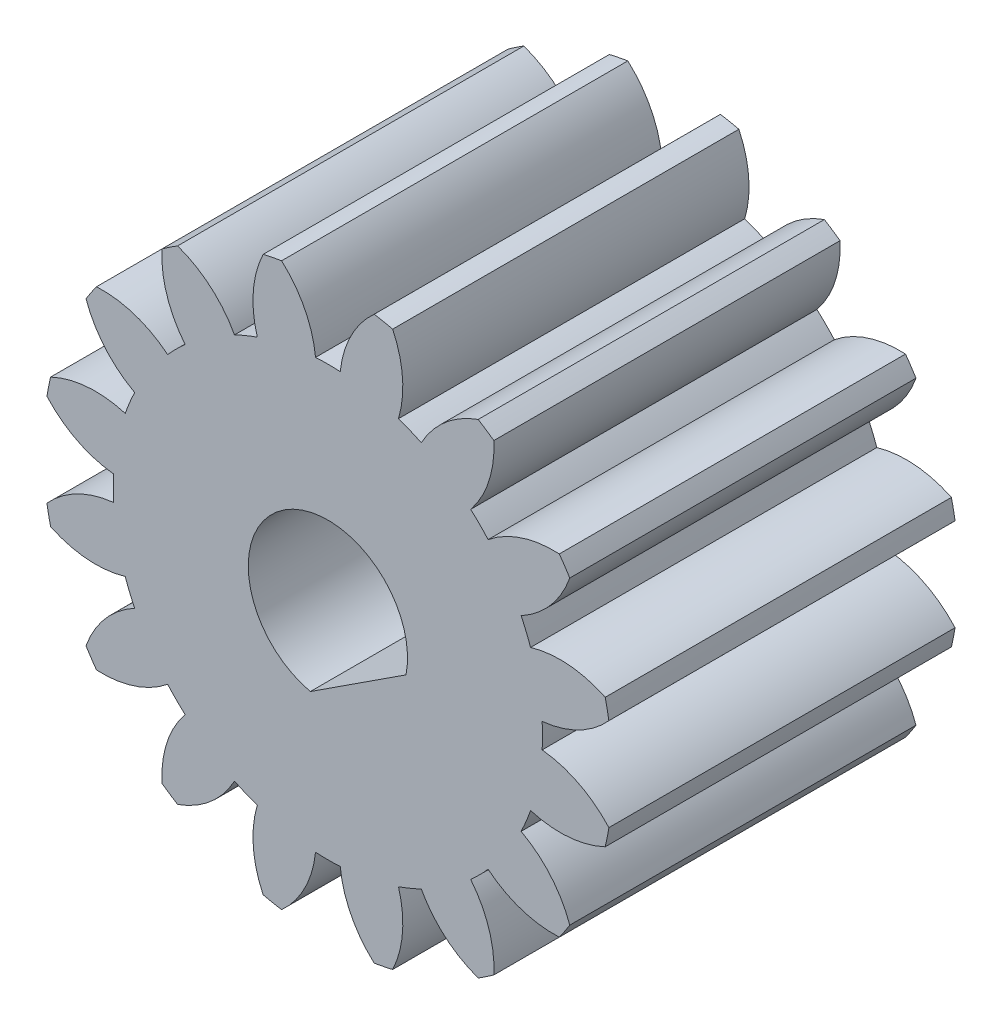
SolidWorks part; units mm, degrees
ref_plane "Front Plane" through (0, 0, 0) normal (0, 0, 1) x (1, 0, 0)
ref_plane "Top Plane" through (0, 0, 0) normal (0, 1, 0) x (1, 0, 0)
ref_plane "Right Plane" through (0, 0, 0) normal (1, 0, 0) x (0, 0, -1)
sketch "Model" plane through (0, 0, 0) normal (0, 0, 1) x (1, 0, 0)
  line L1 (-0.5062, -2.2436) -> (2.2564, -0.4458)
  arc A64 (-8.1156, 1.3371) -> (-6.1887, 0.3566) centre (-5.8806, 3.3458) ccw
  arc A65 (2.2564, -0.4458) -> (-0.5062, -2.2436) centre (0, 0) ccw
  arc A66 (-6.1887, 0.3566) -> (-6.1887, -0.3566) centre (0, 0) ccw
  arc A67 (-6.1887, -0.3566) -> (-8.1156, -1.3371) centre (-5.8806, -3.3458) ccw
  arc A68 (-8.1156, -1.3371) -> (-8.0095, -1.8704) centre (0, 0) ccw
  arc A69 (-8.0095, -1.8704) -> (-5.8541, -2.0388) centre (-6.7134, 0.8407) ccw
  arc A70 (-5.8541, -2.0388) -> (-5.5812, -2.6978) centre (0, 0) ccw
  arc A71 (-5.5812, -2.6978) -> (-6.9862, -4.341) centre (-4.1526, -5.3415) ccw
  arc A72 (-6.9862, -4.341) -> (-6.684, -4.7931) centre (0, 0) ccw
  arc A73 (-6.684, -4.7931) -> (-4.6283, -4.1239) centre (-6.524, -1.7924) ccw
  arc A74 (-4.6283, -4.1239) -> (-4.1239, -4.6283) centre (0, 0) ccw
  arc A75 (-4.1239, -4.6283) -> (-4.7931, -6.684) centre (-1.7924, -6.524) ccw
  arc A76 (-4.7931, -6.684) -> (-4.341, -6.9862) centre (0, 0) ccw
  arc A77 (-4.341, -6.9862) -> (-2.6978, -5.5812) centre (-5.3415, -4.1526) ccw
  arc A78 (-2.6978, -5.5812) -> (-2.0388, -5.8541) centre (0, 0) ccw
  arc A79 (-2.0388, -5.8541) -> (-1.8704, -8.0095) centre (0.8407, -6.7134) ccw
  arc A80 (-1.8704, -8.0095) -> (-1.3371, -8.1156) centre (0, 0) ccw
  arc A81 (-1.3371, -8.1156) -> (-0.3566, -6.1887) centre (-3.3458, -5.8806) ccw
  arc A82 (-0.3566, -6.1887) -> (0.3566, -6.1887) centre (0, 0) ccw
  arc A83 (0.3566, -6.1887) -> (1.3371, -8.1156) centre (3.3458, -5.8806) ccw
  arc A84 (1.3371, -8.1156) -> (1.8704, -8.0095) centre (0, 0) ccw
  arc A85 (1.8704, -8.0095) -> (2.0388, -5.8541) centre (-0.8407, -6.7134) ccw
  arc A86 (2.0388, -5.8541) -> (2.6978, -5.5812) centre (0, 0) ccw
  arc A87 (2.6978, -5.5812) -> (4.341, -6.9862) centre (5.3415, -4.1526) ccw
  arc A88 (4.341, -6.9862) -> (4.7931, -6.684) centre (0, 0) ccw
  arc A89 (4.7931, -6.684) -> (4.1239, -4.6283) centre (1.7924, -6.524) ccw
  arc A90 (4.1239, -4.6283) -> (4.6283, -4.1239) centre (0, 0) ccw
  arc A91 (4.6283, -4.1239) -> (6.684, -4.7931) centre (6.524, -1.7924) ccw
  arc A92 (6.684, -4.7931) -> (6.9862, -4.341) centre (0, 0) ccw
  arc A93 (6.9862, -4.341) -> (5.5812, -2.6978) centre (4.1526, -5.3415) ccw
  arc A94 (5.5812, -2.6978) -> (5.8541, -2.0388) centre (0, 0) ccw
  arc A95 (5.8541, -2.0388) -> (8.0095, -1.8704) centre (6.7134, 0.8407) ccw
  arc A96 (8.0095, -1.8704) -> (8.1156, -1.3371) centre (0, 0) ccw
  arc A97 (8.1156, -1.3371) -> (6.1887, -0.3566) centre (5.8806, -3.3458) ccw
  arc A98 (6.1887, -0.3566) -> (6.1887, 0.3566) centre (0, 0) ccw
  arc A99 (6.1887, 0.3566) -> (8.1156, 1.3371) centre (5.8806, 3.3458) ccw
  arc A100 (8.1156, 1.3371) -> (8.0095, 1.8704) centre (0, 0) ccw
  arc A101 (8.0095, 1.8704) -> (5.8541, 2.0388) centre (6.7134, -0.8407) ccw
  arc A102 (5.8541, 2.0388) -> (5.5812, 2.6978) centre (0, 0) ccw
  arc A103 (5.5812, 2.6978) -> (6.9862, 4.341) centre (4.1526, 5.3415) ccw
  arc A104 (6.9862, 4.341) -> (6.684, 4.7931) centre (0, 0) ccw
  arc A105 (6.684, 4.7931) -> (4.6283, 4.1239) centre (6.524, 1.7924) ccw
  arc A106 (4.6283, 4.1239) -> (4.1239, 4.6283) centre (0, 0) ccw
  arc A107 (4.1239, 4.6283) -> (4.7931, 6.684) centre (1.7924, 6.524) ccw
  arc A108 (4.7931, 6.684) -> (4.341, 6.9862) centre (0, 0) ccw
  arc A109 (4.341, 6.9862) -> (2.6978, 5.5812) centre (5.3415, 4.1526) ccw
  arc A110 (2.6978, 5.5812) -> (2.0388, 5.8541) centre (0, 0) ccw
  arc A111 (2.0388, 5.8541) -> (1.8704, 8.0095) centre (-0.8407, 6.7134) ccw
  arc A112 (1.8704, 8.0095) -> (1.3371, 8.1156) centre (0, 0) ccw
  arc A113 (1.3371, 8.1156) -> (0.3566, 6.1887) centre (3.3458, 5.8806) ccw
  arc A114 (0.3566, 6.1887) -> (-0.3566, 6.1887) centre (0, 0) ccw
  arc A115 (-0.3566, 6.1887) -> (-1.3371, 8.1156) centre (-3.3458, 5.8806) ccw
  arc A116 (-1.3371, 8.1156) -> (-1.8704, 8.0095) centre (0, 0) ccw
  arc A117 (-1.8704, 8.0095) -> (-2.0388, 5.8541) centre (0.8407, 6.7134) ccw
  arc A118 (-2.0388, 5.8541) -> (-2.6978, 5.5812) centre (0, 0) ccw
  arc A119 (-2.6978, 5.5812) -> (-4.341, 6.9862) centre (-5.3415, 4.1526) ccw
  arc A120 (-4.341, 6.9862) -> (-4.7931, 6.684) centre (0, 0) ccw
  arc A121 (-4.7931, 6.684) -> (-4.1239, 4.6283) centre (-1.7924, 6.524) ccw
  arc A122 (-4.1239, 4.6283) -> (-4.6283, 4.1239) centre (0, 0) ccw
  arc A123 (-4.6283, 4.1239) -> (-6.684, 4.7931) centre (-6.524, 1.7924) ccw
  arc A124 (-6.684, 4.7931) -> (-6.9862, 4.341) centre (0, 0) ccw
  arc A125 (-6.9862, 4.341) -> (-5.5812, 2.6978) centre (-4.1526, 5.3415) ccw
  arc A126 (-5.5812, 2.6978) -> (-5.8541, 2.0388) centre (0, 0) ccw
  arc A127 (-5.8541, 2.0388) -> (-8.0095, 1.8704) centre (-6.7134, -0.8407) ccw
  arc A128 (-8.0095, 1.8704) -> (-8.1156, 1.3371) centre (0, 0) ccw
extrude "Boss-Extrude1" add sketch "Model" along normal blind 10
